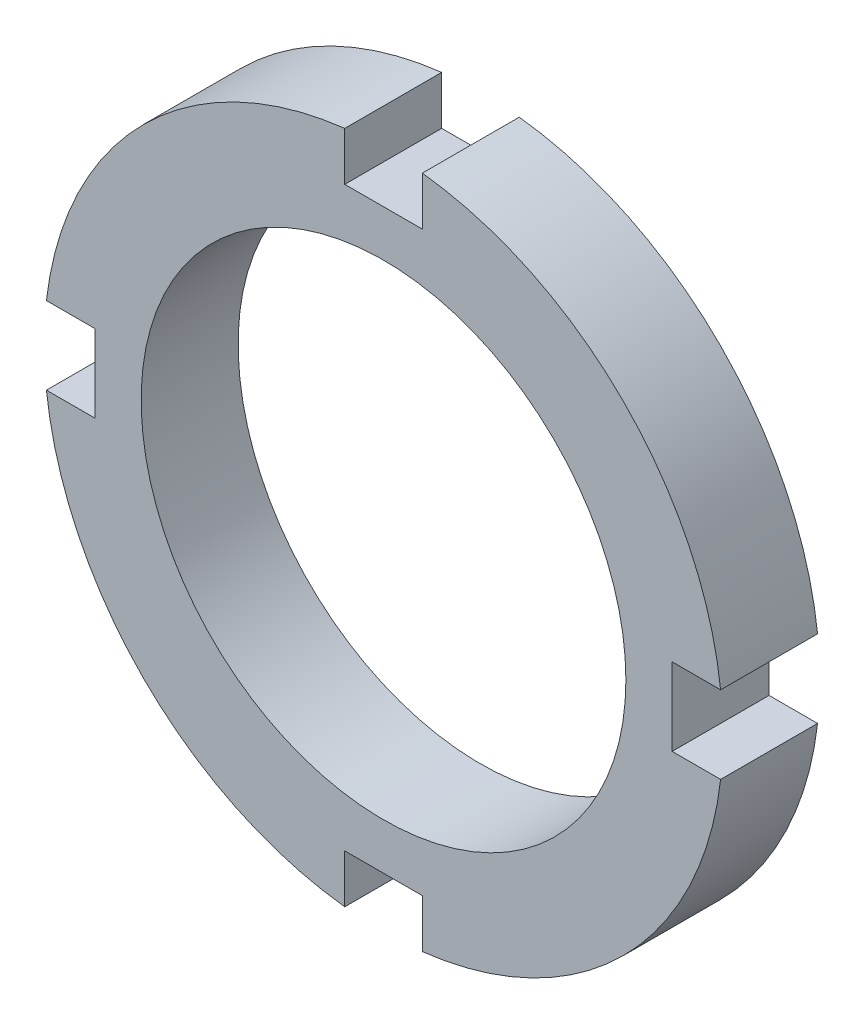
SolidWorks part; units mm, degrees
ref_plane "Front Plane" through (0, 0, 0) normal (0, 0, 1) x (1, 0, 0)
ref_plane "Top Plane" through (0, 0, 0) normal (0, 1, 0) x (1, 0, 0)
ref_plane "Right Plane" through (0, 0, 0) normal (1, 0, 0) x (0, 0, -1)
sketch "Sketch1" plane through (0, 0, 0) normal (0, 0, 1) x (1, 0, 0)
  line L0 (17.3853, 2) -> (14.8853, 2)
  line L1 (14.8853, -2) -> (14.8853, 2)
  line L2 (2, 17.3853) -> (2, 14.8853)
  line L3 (2, 14.8853) -> (-2, 14.8853)
  line L4 (-2, 17.3853) -> (-2, 14.8853)
  line L5 (17.3853, -2) -> (14.8853, -2)
  line L6 (2, -17.3853) -> (2, -14.8853)
  line L7 (-2, -14.8853) -> (2, -14.8853)
  line L8 (-2, -17.3853) -> (-2, -14.8853)
  line L9 (-17.3853, -2) -> (-14.8853, -2)
  line L10 (-14.8853, 2) -> (-14.8853, -2)
  line L11 (-17.3853, 2) -> (-14.8853, 2)
  circle A0 centre (0, 0) radius 12.5
  arc A1 (-2, 17.3853) -> (-17.3853, 2) centre (0, 0) ccw
  arc A2 (-17.3853, -2) -> (-2, -17.3853) centre (0, 0) ccw
  arc A3 (2, -17.3853) -> (17.3853, -2) centre (0, 0) ccw
  arc A4 (17.3853, 2) -> (2, 17.3853) centre (0, 0) ccw
  point P9 (0, 14.8853)
  point P23 (0, 0)
  dimension "D1" = 25
  dimension "D2" = 35
  dimension "D3" = 4
  dimension "D4" = 2.5
  dimension "D5" = 4
extrude "Boss-Extrude1" add sketch "Sketch1" along normal blind 5
